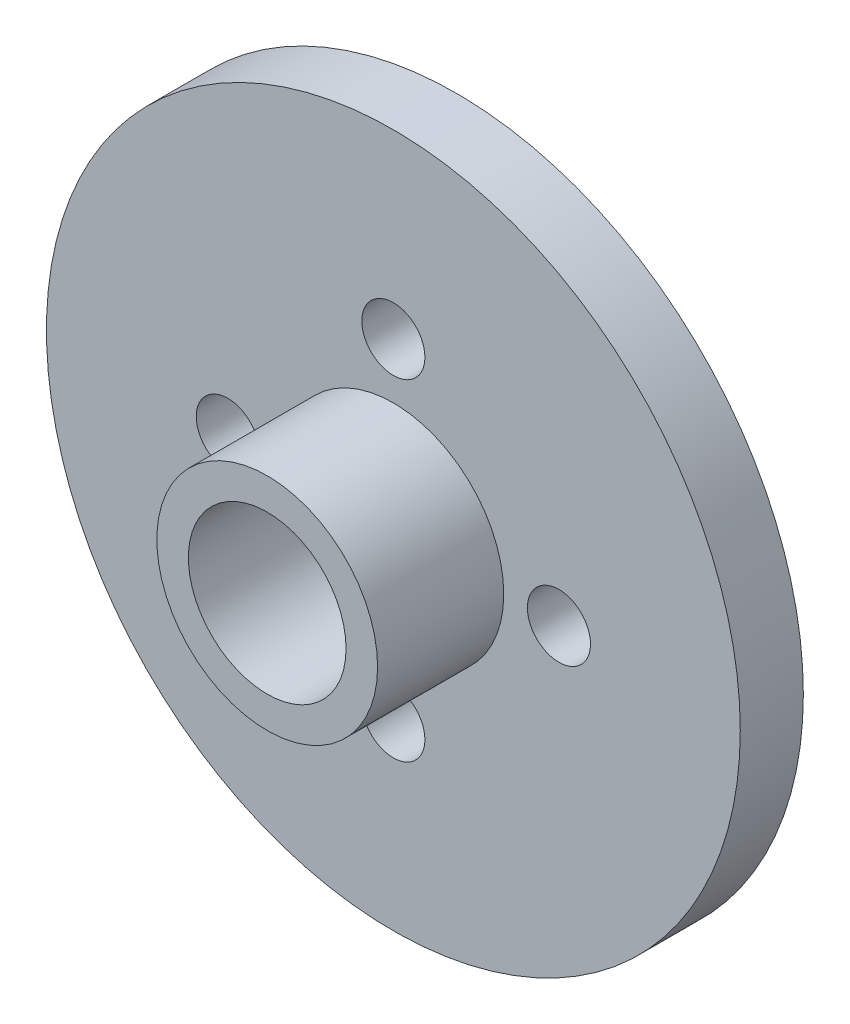
SolidWorks part; units mm, degrees
ref_plane "前视基准面" through (0, 0, 0) normal (0, 0, 1) x (1, 0, 0)
ref_plane "上视基准面" through (0, 0, 0) normal (0, 1, 0) x (1, 0, 0)
ref_plane "右视基准面" through (0, 0, 0) normal (1, 0, 0) x (0, 0, -1)
sketch "草图1" plane through (0, 0, 0) normal (0, 0, 1) x (1, 0, 0)
  circle A0 centre (0, 0) radius 11
  circle A1 centre (0, 0) radius 2.5
  circle A2 centre (5.25, 0) radius 1
  circle A3 centre (0, -5.25) radius 1
  circle A4 centre (-5.25, 0) radius 1
  circle A5 centre (0, 5.25) radius 1
  dimension "D1" = 22
  dimension "D2" = 5
  dimension "D3" = 2
  dimension "D4" = 5.25
  dimension "D5" = 4
extrude "凸台-拉伸1" add sketch "草图1" along normal blind 2
sketch "草图2" plane through (0, 0, 2) normal (0, 0, 1) x (1, 0, 0)
  circle A1 centre (0, 0) radius 3.5
  circle A2 centre (0, 0) radius 2.5
  dimension "D1" = 7
extrude "凸台-拉伸2" add sketch "草图2" along normal blind 4
